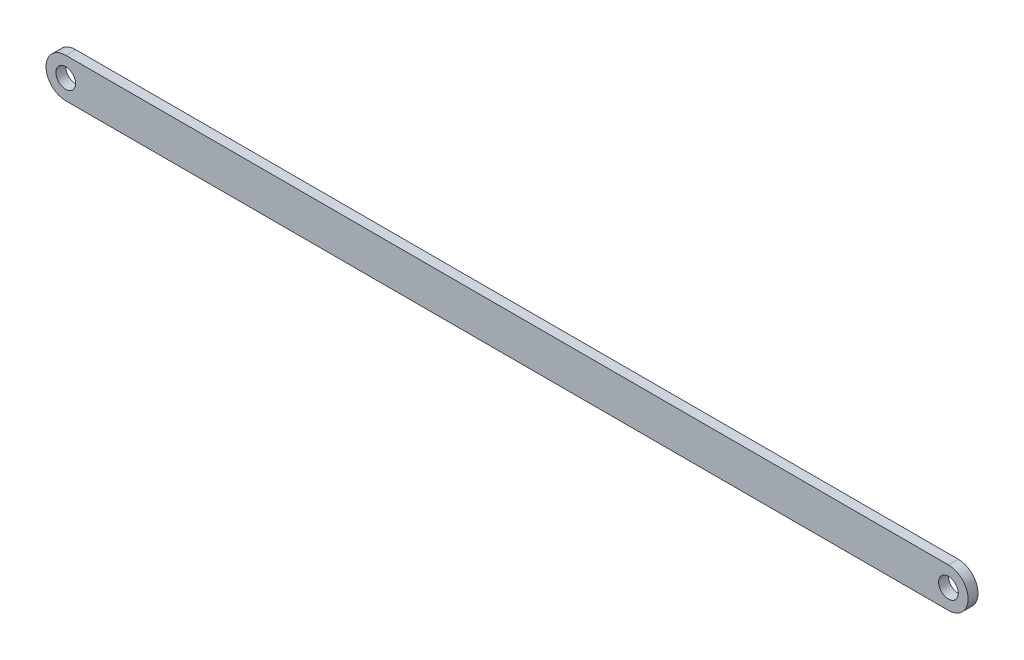
SolidWorks part; units mm, degrees
ref_plane "Plano frontal" through (0, 0, 0) normal (0, 0, 1) x (1, 0, 0)
ref_plane "Plano superior" through (0, 0, 0) normal (0, 1, 0) x (1, 0, 0)
ref_plane "Plano direito" through (0, 0, 0) normal (1, 0, 0) x (0, 0, -1)
sketch "Esboço1" plane through (0, 0, 0) normal (0, 0, 1) x (1, 0, 0)
  line L0 (-44.785, 2) -> (44.785, 2)
  line L1 (-11.9537, 0) -> (11.9537, 0) construction
  line L2 (-44.785, -2) -> (44.785, -2)
  arc A0 (-44.785, 2) -> (-44.785, -2) centre (-44.785, 0) ccw
  arc A1 (44.785, 2) -> (44.785, -2) centre (44.785, 0) cw
  circle A2 centre (-44.785, 0) radius 1
  circle A3 centre (44.785, 0) radius 1
  point P3 (0, 2)
  dimension "D1" = 2
  dimension "D2" = 89.57
extrude "Ressalto-extrusão1" add sketch "Esboço1" along normal blind 1
